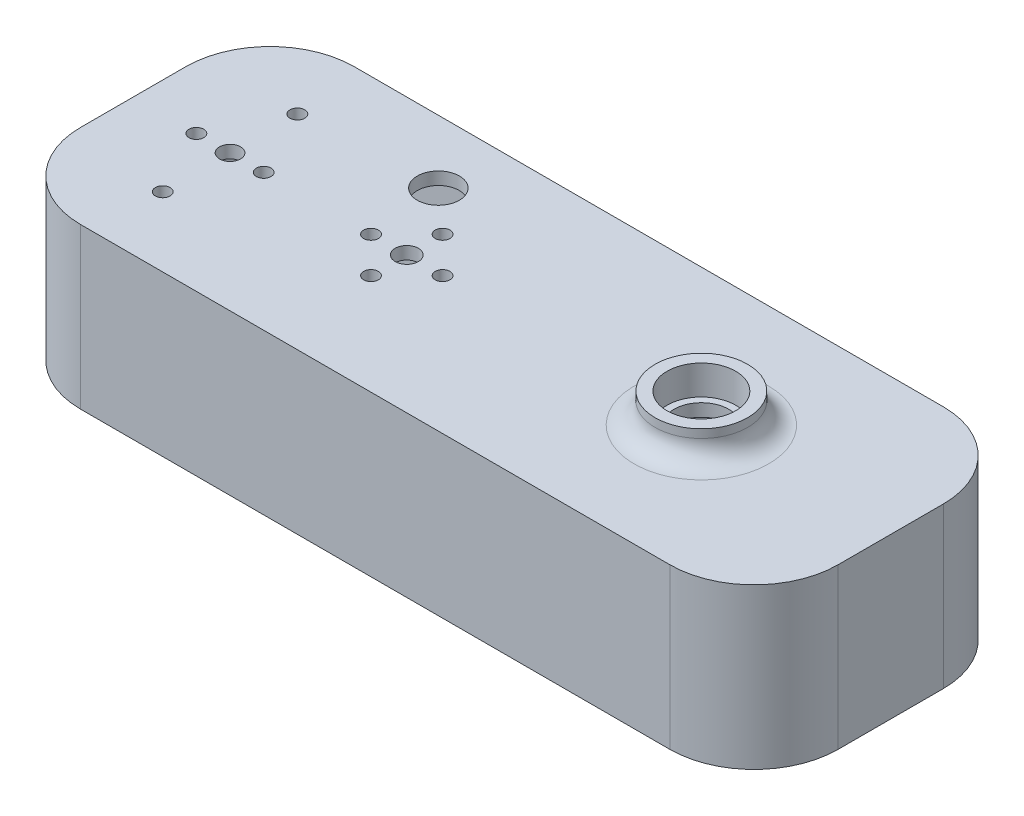
SolidWorks part; units mm, degrees
material "ABS"
ref_plane "Alzado" through (0, 0, 0) normal (0, 0, 1) x (1, 0, 0)
ref_plane "Planta" through (0, 0, 0) normal (0, 1, 0) x (1, 0, 0)
ref_plane "Vista lateral" through (0, 0, 0) normal (1, 0, 0) x (0, 0, -1)
sketch "Croquis1" plane through (0, 0, 0) normal (0, 1, 0) x (1, 0, 0)
  line L0 (100, 0) -> (-100, 0)
  line L2 (90, -32.5) -> (-90, -32.5)
  line L3 (90, -32.5) -> (90, 32.5)
  line L4 (90, 32.5) -> (-90, 32.5)
  line L5 (-90, -32.5) -> (-90, 32.5)
  line L6 (90, -32.5) -> (-90, 32.5) construction
  line L7 (90, 32.5) -> (-90, -32.5) construction
  line L8 (-87, -29.5) -> (87, -29.5)
  line L9 (-87, -29.5) -> (-87, 29.5)
  line L10 (-87, 29.5) -> (87, 29.5)
  line L11 (87, -29.5) -> (87, 29.5)
  line L12 (-87, -29.5) -> (87, 29.5) construction
  line L13 (-87, 29.5) -> (87, -29.5) construction
  point P0 (0, 0)
  point P4 (0, 0)
  point P10 (0, 0)
  dimension "D1" = 200
  dimension "D2" = 65
  dimension "D3" = 3
  dimension "D4" = 3
  dimension "D5" = 180
extrude "Saliente-Extruir1" add sketch "Croquis1" along normal blind 35 contours L11 L8 L9 L0 L5 L2 L3 | L11 L0 L3 L4 L5 L9 L10
sketch "Croquis2" plane through (0, 35, 0) normal (0, 1, 0) x (1, 0, 0)
  line L0 (87, 29.5) -> (67, 29.5)
  line L1 (-87, 29.5) -> (87, 29.5) construction
  line L2 (67, 29.5) -> (87, 9.5)
  line L3 (87, -29.5) -> (87, 29.5) construction
  line L4 (87, 9.5) -> (87, 29.5)
  line L6 (0, 57.1213) -> (0, -50.6023) construction
  line L7 (-84.0687, 0) -> (100.2341, 0) construction
  line L8 (-67, 29.5) -> (-87, 9.5)
  line L9 (-87, 29.5) -> (-67, 29.5)
  line L10 (-87, 9.5) -> (-87, 29.5)
  line L11 (67, -29.5) -> (87, -9.5)
  line L12 (87, -29.5) -> (67, -29.5)
  line L13 (87, -9.5) -> (87, -29.5)
  line L14 (-87, -29.5) -> (-67, -29.5)
  line L15 (-87, -9.5) -> (-87, -29.5)
  line L16 (-67, -29.5) -> (-87, -9.5)
  dimension "D1" = 20
  dimension "D2" = 20
extrude "Saliente-Extruir2" add sketch "Croquis2" against normal blind 35
sketch "Croquis3" plane through (0, 35, 0) normal (0, 1, 0) x (1, 0, 0)
  line L1 (-90, -32.5) -> (90, -32.5)
  line L2 (-90, -32.5) -> (-90, 32.5)
  line L3 (-90, 32.5) -> (90, 32.5)
  line L4 (90, -32.5) -> (90, 32.5)
  line L5 (-90, -32.5) -> (90, 32.5) construction
  line L6 (-90, 32.5) -> (90, -32.5) construction
  point P0 (0, 0)
extrude "Saliente-Extruir3" add sketch "Croquis3" along normal blind 3
fillet "Redondeo1" radius 20 4 edges at (90, 19, -32.5) (-90, 19, -32.5) (-90, 19, 32.5) (90, 19, 32.5)
sketch "Croquis5" plane through (0, 35, 0) normal (0, -1, 0) x (1, 0, 0)
  line L0 (-87, 9.5) -> (-87, -9.5) construction
  line L1 (90, 12.5) -> (90, -12.5) construction
  circle A0 centre (-67, 0) radius 2.5
  circle A1 centre (-67, 0) radius 11
  circle A2 centre (45, 0) radius 27.5
  circle A3 centre (-25, 0) radius 6.5
  circle A4 centre (-25, 0) radius 2.75
  circle A5 centre (45, 0) radius 2.75
  dimension "D1" = 5
  dimension "D2" = 20
  dimension "D3" = 22
  dimension "D4" = 55
  dimension "D5" = 13
  dimension "D6" = 70
  dimension "D7" = 45
  dimension "D8" = 5.5
  dimension "D9" = 5.5
extrude "Cortar-Extruir1" cut sketch "Croquis5" against normal blind 3 contours A5 | A4 | A0
sketch "Croquis7" plane through (0, 35, 0) normal (0, -1, 0) x (1, 0, 0)
  line L0 (-75, 0) -> (-59, 0)
  line L1 (-67, -16) -> (-67, 16)
  circle A0 centre (-67, 0) radius 2.5 construction
  circle A1 centre (-67, 16) radius 1.75
  circle A2 centre (-59, 0) radius 1.75
  circle A3 centre (-67, -16) radius 1.75
  circle A4 centre (-75, 0) radius 1.75
  point P5 (-67, 0)
  point P10 (-67, 0)
  dimension "D4" = 3.5
  dimension "D5" = 3.5
  dimension "D6" = 3.5
  dimension "D7" = 3.5
  dimension "D1" = 16
  dimension "D2" = 0
  dimension "D3" = 32
extrude "Cortar-Extruir3" cut sketch "Croquis7" against normal up to next
sketch "Croquis8" plane through (0, 0, 0) normal (0, -1, 0) x (1, 0, 0)
  line L0 (-90, 12.5) -> (-90, -12.5) construction
  line L1 (70, 32.5) -> (-70, 32.5) construction
  line L2 (0, 53.2778) -> (0, -50.5966) construction
  line L3 (-119.4777, 0) -> (131.9812, 0) construction
  circle A0 centre (-80, 22.5) radius 1.8937
  circle A1 centre (80, 22.5) radius 1.8937
  circle A2 centre (-80, -22.5) radius 1.8937
  circle A3 centre (80, -22.5) radius 1.8937
  point P0 (-80, 22.5)
  point P11 (80, 22.5)
  point P13 (-80, -22.5)
  point P15 (80, -22.5)
  dimension "D1" = 10
  dimension "D2" = 10
hole_wizard "Taladro de margen para M31" positions "Croquis8" profile "Croquis9" hole size "M3" standard "GB"
sketch "Croquis9" plane through (-80, 0, 22.5) normal (1, 0, 0) x (0, 0, -1)
  line L0 (0, 0) -> (0, 31.0215)
  line L1 (0, 31.0215) -> (1.7, 30)
  line L2 (1.7, 30) -> (1.7, 0)
  line L5 (1.7, 0) -> (0, 0)
  line L10 (0, 31.0215) -> (-1.7, 30) construction
  line L11 (0, -6.35) -> (0, 107.95) construction
  dimension "Di醡etro de taladro" = 3.4
  dimension "Profundidad de taladro" = 30
  dimension "羘gulo de perforador" = 118
sketch "Croquis10" plane through (0, 38, 0) normal (0, 1, 0) x (1, 0, 0)
  line L0 (-33.5, 0) -> (-16.5, 0)
  line L1 (-25, -8.5) -> (-25, 8.5)
  circle A0 centre (-25, 0) radius 2.75 construction
  circle A1 centre (-25, 8.5) radius 1.75
  circle A2 centre (-16.5, 0) radius 1.75
  circle A3 centre (-25, -8.5) radius 1.75
  circle A4 centre (-33.5, 0) radius 1.75
  point P5 (-25, 0)
  point P10 (-25, 0)
  dimension "D4" = 3.5
  dimension "D5" = 3.5
  dimension "D6" = 3.5
  dimension "D7" = 3.5
  dimension "D1" = 17
  dimension "D2" = 0
  dimension "D3" = 17
extrude "Cortar-Extruir4" cut sketch "Croquis10" against normal up to next
sketch "Croquis11" plane through (0, 35, 0) normal (0, -1, 0) x (1, 0, 0)
  line L0 (70, -32.5) -> (-70, -32.5) construction
  line L1 (-90, 12.5) -> (-90, -12.5) construction
  circle A0 centre (-35, -17.5) radius 5
  dimension "D1" = 10
  dimension "D2" = 15
  dimension "D3" = 55
extrude "Cortar-Extruir5" cut sketch "Croquis11" against normal blind 10
sketch "Croquis12" plane through (0, 38, 0) normal (0, 1, 0) x (1, 0, 0)
  circle A0 centre (45, 0) radius 6.5
  dimension "D1" = 13
extrude "Cortar-Extruir6" cut sketch "Croquis12" against normal blind 10
sketch "Croquis13" plane through (0, 38, 0) normal (0, 1, 0) x (1, 0, 0)
  circle A0 centre (45, 0) radius 11
  circle A1 centre (45, 0) radius 8.15
  dimension "D1" = 22
  dimension "D2" = 16.3
extrude "Saliente-Extruir4" add sketch "Croquis13" along normal blind 7
fillet "Redondeo2" radius 5 1 edges at (45, 38, -11)
sketch "Croquis14" plane through (0, 35, 0) normal (0, -1, 0) x (1, 0, 0)
  circle A0 centre (45, 0) radius 6.5
  circle A1 centre (-25, 0) radius 2.75
  dimension "D1" = 70
